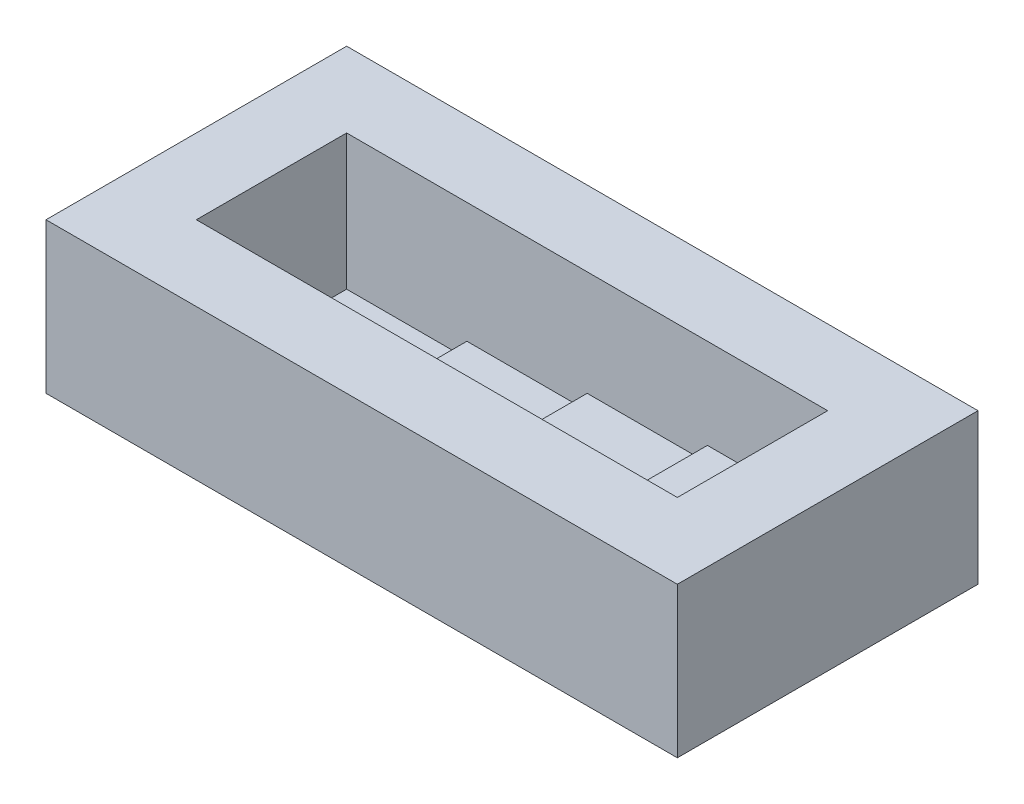
SolidWorks part; units mm, degrees
ref_plane "Front Plane" through (0, 0, 0) normal (0, 0, 1) x (1, 0, 0)
ref_plane "Top Plane" through (0, 0, 0) normal (0, 1, 0) x (1, 0, 0)
ref_plane "Right Plane" through (0, 0, 0) normal (1, 0, 0) x (0, 0, -1)
sketch "Sketch3" plane through (0, 0, 0) normal (0, 0, 1) x (1, 0, 0)
  line L0 (32, 4) -> (32, 0)
  line L1 (0, 0) -> (20, 0)
  line L2 (0, 0) -> (0, 1)
  line L3 (0, 1) -> (8, 1)
  line L5 (20, 0) -> (32, 0)
  line L6 (8, 1) -> (8, 2)
  line L7 (8, 2) -> (16, 2)
  line L10 (16, 2) -> (16, 3)
  line L11 (16, 3) -> (24, 3)
  line L14 (24, 3) -> (24, 4)
  line L15 (24, 4) -> (32, 4)
  dimension "D1" = 8
  dimension "D2" = 8
  dimension "D3" = 8
  dimension "D4" = 8
  dimension "D5" = 1
  dimension "D6" = 1
  dimension "D7" = 1
  dimension "D8" = 1
extrude "Boss-Extrude1" add sketch "Sketch3" along normal blind 10
sketch "Sketch6" plane through (0, 0, 0) normal (1, 0, 0) x (0, 0, -1)
  line L1 (0, 0) -> (-10, 0)
  line L2 (0, 0) -> (0, 10)
  line L3 (0, 10) -> (-10, 10)
  line L4 (-10, 0) -> (-10, 10)
  dimension "D1" = 10
  dimension "D2" = 10
extrude "Boss-Extrude2" add sketch "Sketch6" against normal blind 5
sketch "Sketch7" plane through (0, 0, 0) normal (0, 0, -1) x (-1, 0, 0)
  line L1 (5, 10) -> (-32, 10)
  line L2 (5, 10) -> (5, 0)
  line L3 (5, 0) -> (-32, 0)
  line L4 (-32, 10) -> (-32, 0)
extrude "Boss-Extrude3" add sketch "Sketch7" along normal blind 5
sketch "Sketch8" plane through (32, 0, 0) normal (1, 0, 0) x (0, 0, -1)
  line L1 (-10, 0) -> (5, 0)
  line L2 (-10, 0) -> (-10, 10)
  line L3 (-10, 10) -> (5, 10)
  line L4 (5, 0) -> (5, 10)
extrude "Boss-Extrude4" add sketch "Sketch8" along normal blind 5
sketch "Sketch9" plane through (0, 0, 10) normal (0, 0, 1) x (1, 0, 0)
  line L1 (-5, 0) -> (37, 0)
  line L2 (-5, 0) -> (-5, 10)
  line L3 (-5, 10) -> (37, 10)
  line L4 (37, 0) -> (37, 10)
extrude "Boss-Extrude5" add sketch "Sketch9" along normal blind 5
